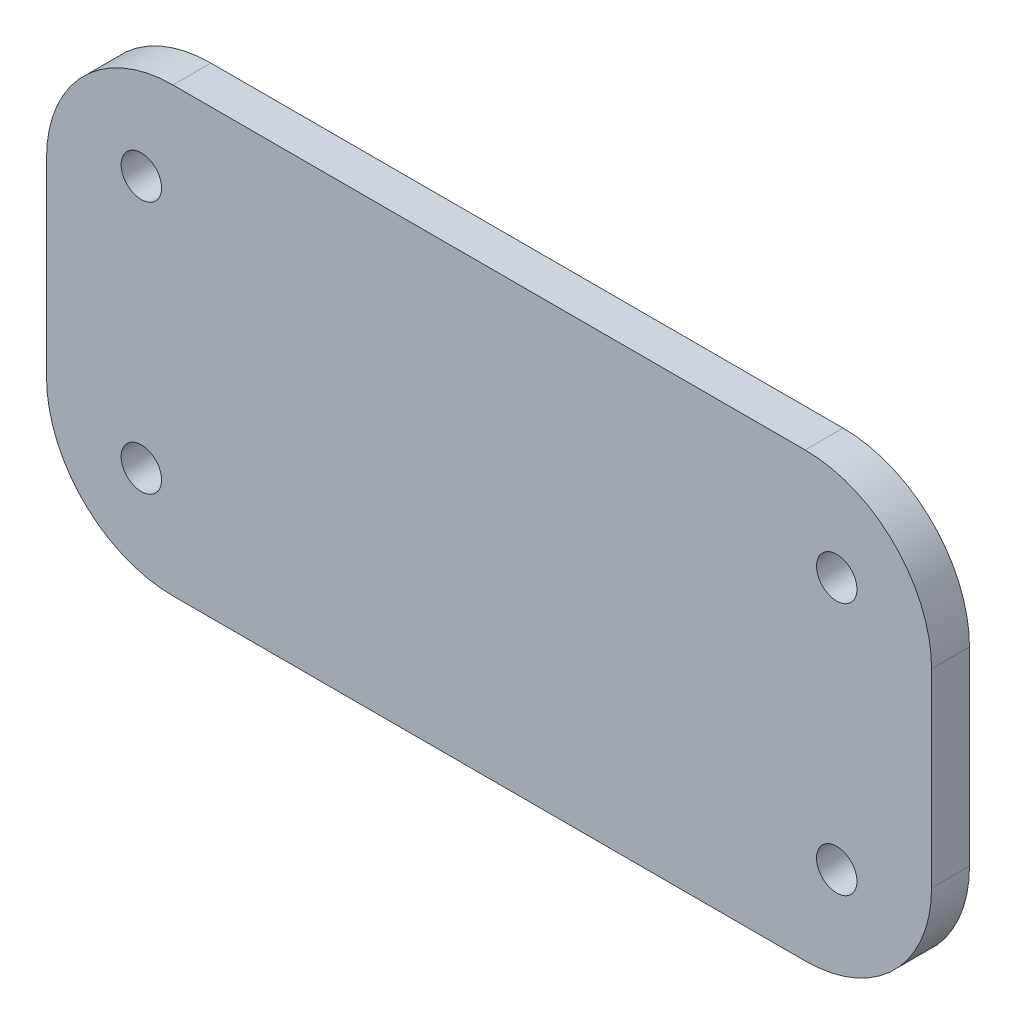
SolidWorks part; units mm, degrees
ref_plane "前视基准面" through (0, 0, 0) normal (0, 0, 1) x (1, 0, 0)
ref_plane "上视基准面" through (0, 0, 0) normal (0, 1, 0) x (1, 0, 0)
ref_plane "右视基准面" through (0, 0, 0) normal (1, 0, 0) x (0, 0, -1)
sketch "草图1" plane through (0, 0, 0) normal (0, 0, 1) x (1, 0, 0)
  line L1 (-35, -17.5) -> (35, -17.5)
  line L2 (-35, -17.5) -> (-35, 17.5)
  line L3 (-35, 17.5) -> (35, 17.5)
  line L4 (35, -17.5) -> (35, 17.5)
  line L5 (-35, -17.5) -> (35, 17.5) construction
  line L6 (-35, 17.5) -> (35, -17.5) construction
  line L7 (-27.5, -10) -> (27.5, -10) construction
  line L8 (-27.5, -10) -> (-27.5, 10) construction
  line L9 (-27.5, 10) -> (27.5, 10) construction
  line L10 (27.5, -10) -> (27.5, 10) construction
  line L11 (-27.5, -10) -> (27.5, 10) construction
  line L12 (-27.5, 10) -> (27.5, -10) construction
  circle A0 centre (-27.5, 10) radius 1.6
  circle A1 centre (-27.5, -10) radius 1.6
  circle A2 centre (27.5, -10) radius 1.6
  circle A3 centre (27.5, 10) radius 1.6
  point P0 (0, 0)
  point P6 (0, 0)
  dimension "D1" = 3.2
  dimension "D4" = 7.5
  dimension "D5" = 7.5
  dimension "D2" = 55
  dimension "D3" = 20
extrude "凸台-拉伸1" add sketch "草图1" along normal blind 3
fillet "圆角1" radius 10 4 edges at (35, -17.5, 1.5) (-35, -17.5, 1.5) (35, 17.5, 1.5) (-35, 17.5, 1.5)
